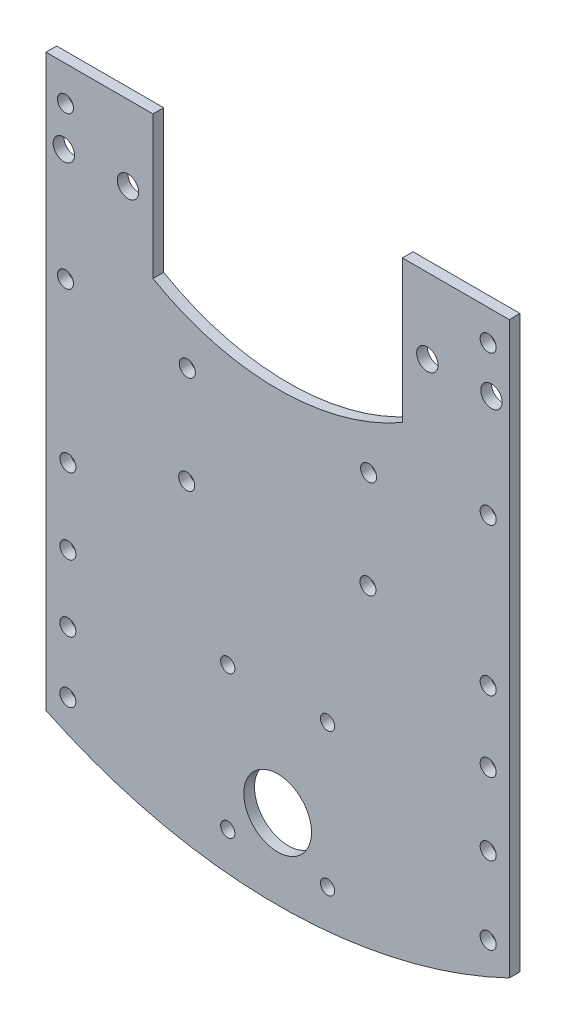
SolidWorks part; units mm, degrees
material "6063-O"
ref_plane "Front Plane" through (0, 0, 0) normal (0, 0, 1) x (1, 0, 0)
ref_plane "Top Plane" through (0, 0, 0) normal (0, 1, 0) x (1, 0, 0)
ref_plane "Right Plane" through (0, 0, 0) normal (1, 0, 0) x (0, 0, -1)
sketch "Sketch1" plane through (0, 0, 0) normal (0, 0, 1) x (1, 0, 0)
  line L1 (-34.1797, 1.6565) -> (-34.1797, 41.6565)
  line L2 (-34.1797, 41.6565) -> (-64.1797, 41.6565)
  line L3 (-64.1797, 41.6565) -> (-64.1797, -118.3435)
  line L5 (65.8203, -118.3435) -> (65.8203, 41.6565)
  line L6 (65.8203, 41.6565) -> (35.8203, 41.6565)
  line L7 (35.8203, 41.6565) -> (35.8203, 1.6565)
  arc A0 (-34.1797, 1.6565) -> (35.8203, 1.6565) centre (0.8203, 62.2783) ccw
  arc A1 (-64.1797, -118.3435) -> (65.8203, -118.3435) centre (0.8203, 16.8416) ccw
  circle A2 centre (60.8203, 20.5545) radius 3
  circle A3 centre (42.8203, 20.5545) radius 3
  circle A4 centre (-59.1797, 20.5545) radius 3
  circle A5 centre (-41.1797, 20.5545) radius 3
  point P4 (0, 0)
  point P16 (0, 0)
  dimension "D7" = 70
  dimension "D8" = 150
  dimension "D9" = 6
  dimension "D10" = 6
  dimension "D1" = 130
  dimension "D2" = 30
  dimension "D3" = 30
  dimension "D4" = 40
  dimension "D5" = 40
  dimension "D6" = 160
  dimension "D12" = 18
  dimension "D13" = 84
  dimension "D14" = 18
  dimension "D15" = 160
  dimension "D16" = 21.1021
  dimension "D17" = 41.1797
extrude "Boss-Extrude2" add sketch "Sketch1" along normal blind 3
sketch "Sketch4" plane through (0, 0, 3) normal (0, 0, 1) x (1, 0, 0)
  line L0 (-34.1797, 1.6565) -> (65.8203, -118.3435) construction
  line L2 (35.8203, 1.6565) -> (-64.1797, -118.3435) construction
  line L4 (0.8203, -7.7217) -> (0.8203, -164.587) construction
  circle A4 centre (0.8203, -110.7217) radius 9.5
  arc A5 (-34.1797, 1.6565) -> (35.8203, 1.6565) centre (0.8203, 62.2783) ccw construction
  point P0 (0.8203, -110.7217)
  point P17 (0.8203, -68.979)
  dimension "D4" = 19
  dimension "D1" = 103
extrude "Cut-Extrude2" cut sketch "Sketch4" against normal blind 10
sketch "Sketch5" plane through (0, 0, 0) normal (0, 0, -1) x (-1, 0, 0)
  circle A4 centre (-14.8203, -121.7217) radius 2 construction
  circle A5 centre (-14.8203, -121.7217) radius 2
  circle A6 centre (-14.8203, -81.7217) radius 2 construction
  circle A7 centre (13.1797, -81.7217) radius 2 construction
  circle A8 centre (13.1797, -121.7217) radius 2 construction
  circle A9 centre (-14.8203, -81.7217) radius 2
  circle A10 centre (13.1797, -81.7217) radius 2
  circle A11 centre (13.1797, -121.7217) radius 2
extrude "Cut-Extrude3" cut sketch "Sketch5" against normal up to surface (3 mm away) up to face at (10.3203, -110.7217, 3)
sketch "Sketch6" plane through (0, 0, 0) normal (0, 0, -1) x (-1, 0, 0)
  circle A0 centre (-26.1701, -42.8703) radius 2.25
  circle A1 centre (-26.3397, -15.2903) radius 2.25
  circle A2 centre (24.5295, -15.2903) radius 2.25
  circle A3 centre (24.6991, -42.8703) radius 2.25
  dimension "D1" = 4.5
  dimension "D2" = 4.5
  dimension "D3" = 4.5
  dimension "D4" = 4.5
extrude "Cut-Extrude4" cut sketch "Sketch6" against normal up to surface (3 mm away) up to face at (-11.1797, -121.7217, 3)
sketch "Sketch7" plane through (0, 0, 3) normal (0, 0, 1) x (1, 0, 0)
  circle A0 centre (-58.0508, -112.0762) radius 2.25
  circle A1 centre (-58.0508, -94.9619) radius 2.25
  circle A2 centre (-58.0508, -76.2503) radius 2.25
  circle A3 centre (-58.0508, -55.0286) radius 2.25
  circle A4 centre (-58.7353, -10.7596) radius 2.25
  circle A5 centre (-58.7353, 31.9013) radius 2.25
  circle A6 centre (59.8927, -112.1154) radius 2.25
  circle A7 centre (59.8927, -90.4056) radius 2.25
  circle A8 centre (59.8927, -70.122) radius 2.25
  circle A9 centre (59.8927, -50.2558) radius 2.25
  circle A10 centre (59.8927, -8.8259) radius 2.25
  circle A11 centre (59.8927, 33.0331) radius 2.25
extrude "Cut-Extrude5" cut sketch "Sketch7" against normal blind 10
